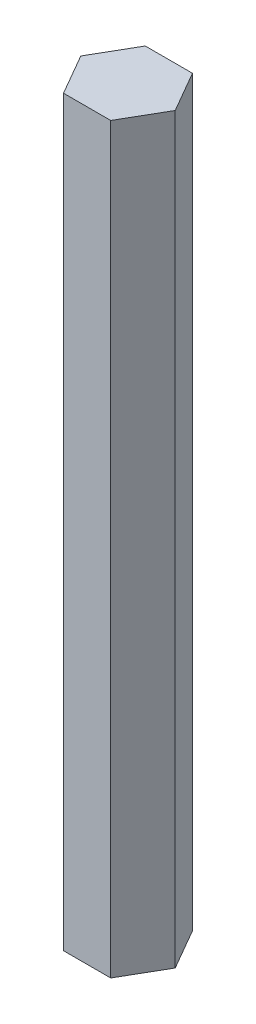
SolidWorks part; units mm, degrees
ref_plane "Front Plane" through (0, 0, 0) normal (0, 0, 1) x (1, 0, 0)
ref_plane "Top Plane" through (0, 0, 0) normal (0, 1, 0) x (1, 0, 0)
ref_plane "Right Plane" through (0, 0, 0) normal (1, 0, 0) x (0, 0, -1)
sketch "Sketch1" plane through (0, 0, 0) normal (0, 1, 0) x (1, 0, 0)
  line L1 (1.7321, 0) -> (0.866, 1.5)
  line L2 (0.866, 1.5) -> (-0.866, 1.5)
  line L3 (-0.866, 1.5) -> (-1.7321, 0)
  line L4 (-1.7321, 0) -> (-0.866, -1.5)
  line L5 (-0.866, -1.5) -> (0.866, -1.5)
  line L6 (0.866, -1.5) -> (1.7321, 0)
  circle A0 centre (0, 0) radius 1.5 construction
  dimension "D1" = 3
extrude "Boss-Extrude1" add sketch "Sketch1" along normal up to surface (16.55 mm away) and the other way offset from surface (10.702 mm away) 16
